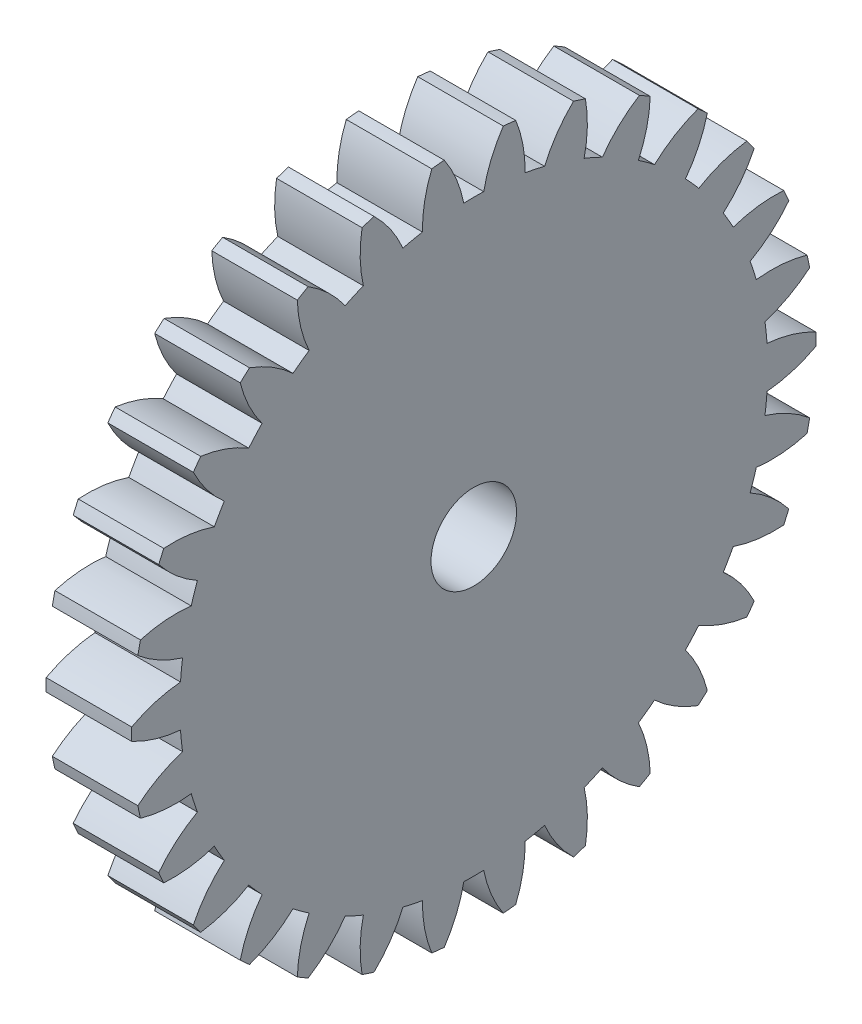
SolidWorks part; units mm, degrees
ref_plane "Plane1" through (0, 0, 0) normal (0, 0, 1) x (1, 0, 0)
ref_plane "Plane2" through (0, 0, 0) normal (0, 1, 0) x (1, 0, 0)
ref_plane "Plane3" through (0, 0, 0) normal (1, 0, 0) x (0, 0, -1)
other "Configuration Table"
sketch "HoldingSke" plane through (0, 0, 0) normal (0, 1, 0) x (1, 0, 0)
  line L0 (0, 0) -> (0.866, -0.5)
  line L1 (-15, 0) -> (100, 0) construction
  line L2 (0, 0) -> (-2.1039, 2.3779)
  line L3 (0, 0) -> (-11.863, 4.5341)
  line L4 (0, 0) -> (7.479, 4.318)
  line L5 (0, 0) -> (-46.8476, -17.4728)
  line L6 (0, 0) -> (-3.3159, -2.2372)
  line L7 (-2.1039, 2.3779) -> (8.6586, 51.2059)
  line L8 (-76.2, 54.61) -> (-75.5, 54.61)
  line L9 (-71.009, 38.7566) -> (-53.1078, 45.2721)
  line L10 (-76.2, 71.12) -> (104.1128, 71.12)
  line L11 (0, 0) -> (-4, 0)
  line L12 (-76.2, 101.6) -> (-76.162, 101.6)
  line L13 (24.9733, 27.94) -> (52.9518, 28.4284)
  line L14 (24.9733, 27.94) -> (24.9743, 27.94)
  line L15 (24.9733, 27.94) -> (100.4006, 29.5858)
  line L16 (-63.627, -1) -> (-12.827, -1)
  circle A0 centre (0, 0) radius 2
  circle A1 centre (0, 0) radius 13.749
  circle A2 centre (0, 0) radius 37.5
  circle A3 centre (0, 0) radius 2
  dimension "MHD" = 27.498
  dimension "Hub_dia" = 75
  dimension "Bore" = 4
  dimension "MBD" = 4
  dimension "Num_teeth" = 30
  dimension "Pitch" = 1
  dimension "Overall_len" = 50
  dimension "Show_teeth" = 30
  dimension "Thickness" = 4
  dimension "OAL" = 50.0001
  dimension "T_dim" = 0.7
  dimension "Ap" = 20
  dimension "H" = 19.05
  dimension "Pitch_radius" = 180.3128
  dimension "Width" = 4
  dimension "Backlash" = 0.038
  dimension "Addendum_fac" = 1
  dimension "Dedendum_fac" = 1.25
  dimension "Clearance_fac" = 0.25
  dimension "Dedendum_add" = 0.001
  dimension "Module" = 1
sketch "BasProSke" plane through (0, 0, 0) normal (0, 1, 0) x (1, 0, 0)
  line L0 (-10, 0) -> (60, 0) construction
  line L1 (0, 0) -> (0, 16)
  line L2 (0, 0) -> (4, 0)
  line L3 (4, 0) -> (4, 16)
  line L4 (4, 16) -> (0, 16)
  dimension "Thickness" = 4
  dimension "Diameter" = 32
revolve "Base-Revolve" add sketch "BasProSke" angle 360 about L0
sketch "TooCutSke" plane through (0, 0, 0) normal (1, 0, 0) x (0, 0, -1)
  line L1 (0, 0) -> (0, 107) construction
  line L2 (0, 0) -> (-0.8515, 14.9758) construction
  line L3 (0, 0) -> (-3.1323, 29.8014) construction
  line L4 (-0.8515, 14.9758) -> (-1.5661, 14.9007) construction
  arc A0 (0.4664, 13.7411) -> (-0.4664, 13.7411) centre (0, 0) ccw
  arc A1 (1.3975, 15.9644) -> (-1.3975, 15.9644) centre (0, 0) ccw
  circle A2 centre (0, 0) radius 15 construction
  circle A3 centre (0, 0) radius 14.0954 construction
  arc A4 (-0.4664, 13.7411) -> (-1.3975, 15.9644) centre (-6.3534, 12.5823) ccw
  arc A5 (1.3975, 15.9644) -> (0.4664, 13.7411) centre (6.3534, 12.5823) ccw
  dimension "Root_dia" = 27.498
  dimension "Overcut_dia" = 32.0508
  dimension "Pitch_dia" = 30
  dimension "Base_dia" = 28.1908
  dimension "Flank_rad" = 6
  dimension "Half_ang" = 6
  dimension "Half_CT" = 0.7185
extrude "ToothCut" cut sketch "TooCutSke" along normal through all
fillet "Breaks" [suppressed] radius 0.02
fillet "RootFillets" [suppressed] radius 0.251
pattern_circular "TeethCuts" count 30 every 12 about axis through (-10, 0, 0) along (1, 0, 0) of "ToothCut", "RootFillets", "Breaks"
sketch "HubNeaOneSke" plane through (0, 0, 0) normal (-1, 0, 0) x (0, 0, 1)
  circle A0 centre (0, 0) radius 13.749
  dimension "Diameter" = 27.498
extrude "HubNearOne" [suppressed] add sketch "HubNeaOneSke" along normal blind 46.0001
sketch "HubNeaBotSke" plane through (0, 0, 0) normal (-1, 0, 0) x (0, 0, 1)
  circle A0 centre (0, 0) radius 13.749
  dimension "Diameter" = 27.498
extrude "HubNearBoth" [suppressed] add sketch "HubNeaBotSke" along normal blind 23
ref_plane "FarPln" through (4, 0, 0) normal (1, 0, 0) x (0, 0, -1)
sketch "HubFarSke" plane through (4, 0, 0) normal (1, 0, 0) x (0, 0, -1)
  circle A0 centre (0, 0) radius 13.749
  dimension "Diameter" = 27.498
extrude "HubFar" [suppressed] add sketch "HubFarSke" along normal blind 23
sketch "BorSke" plane through (0, 0, 0) normal (1, 0, 0) x (0, 0, -1)
  circle A0 centre (0, 0) radius 2
  dimension "Diameter" = 4
extrude "Bore" cut sketch "BorSke" along normal mid plane 100.0001
sketch "KeySke" plane through (0, 0, 0) normal (1, 0, 0) x (0, 0, -1)
  line L0 (-0.8, 0) -> (-0.8, 2.7)
  line L1 (-0.8, 2.7) -> (0.8, 2.7)
  line L2 (0.8, 2.7) -> (0.8, 0)
  line L3 (0, 0) -> (0, 34) construction
  line L4 (-0.8, 0) -> (0.8, 0)
  dimension "Offset" = 2.7
  dimension "Width" = 1.6
extrude "Keyway" [suppressed] cut sketch "KeySke" along normal mid plane 100.0001
pattern_circular "Keyway2" [suppressed] count 2 every 90 about axis through (-10, 0, 0) along (1, 0, 0)
equation "' \"Module@HoldingSke\" = 6.35"
equation "' \"Num_teeth@HoldingSke\" = 12"
equation "' \"Ap@HoldingSke\" =  20"
equation "' \"Ap@HoldingSke\" = 20"
equation "' \"Width@HoldingSke\" = 0.5 * 25.4"
equation "' \"Hub_dia@HoldingSke\"= 1 * 25.4"
equation "' \"Hub_dia@HoldingSke\" = 1 * 25.4"
equation "' \"Overall_len@HoldingSke\" = 1.0 * 25.4"
equation "' \"Bore@HoldingSke\" = 0.75 * 25.4"
equation "' \"T_dim@HoldingSke\" = 0.1 * 25.4"
equation "' \"Width@KeySke\" = 0.25 * 25.4"
equation "' \"Show_teeth@HoldingSke\" = 13"
equation "' \"Backlash@HoldingSke\" = 0.009 * 25.4"
equation "' \"Addendum_fac@HoldingSke\" = 1.0"
equation "' \"Dedendum_fac@HoldingSke\" = 1.25"
equation "' \"Dedendum_add@HoldingSke\" = 0.00005 * 25.4"
equation "' \"Clearance_fac@HoldingSke\" = 0.25"
equation "\"Pitch@HoldingSke\" = 1 / \"Module@HoldingSke\""
equation "\"Overcut_dia@TooCutSke\" = (\"Num_teeth@HoldingSke\" + 2 * \"Addendum_fac@HoldingSke\") / \"Pitch@HoldingSke\" + 0.002 * 25.4"
equation "\"Pitch_dia@TooCutSke\" = \"Num_teeth@HoldingSke\" / \"Pitch@HoldingSke\""
equation "\"Base_dia@TooCutSke\" = \"Num_teeth@HoldingSke\" / \"Pitch@HoldingSke\" * cos((\"Ap@HoldingSke\"  * 3.14159265 / 180))"
equation "\"Root_dia@TooCutSke\" = (\"Num_teeth@HoldingSke\" + 2) / \"Pitch@HoldingSke\" - 2 * (\"Addendum_fac@HoldingSke\" + \"Dedendum_fac@HoldingSke\") / \"Pitch@HoldingSke\" - \"Dedendum_add@HoldingSke\" * 2"
equation "\"Half_ang@TooCutSke\" = 180 / \"Num_teeth@HoldingSke\""
equation "\"Half_CT@TooCutSke\" = \"Num_teeth@HoldingSke\" / \"Pitch@HoldingSke\" * sin((3.14159265 / 2 / \"Num_teeth@HoldingSke\")) / 2 - 7 * \"Backlash@HoldingSke\" / 4"
equation "\"Flank_rad@TooCutSke\" = \"Num_teeth@HoldingSke\" / \"Pitch@HoldingSke\" / 5"
equation "\"Radius@RootFillets\" = \"Clearance_fac@HoldingSke\" / \"Pitch@HoldingSke\" + \"Dedendum_add@HoldingSke\""
equation "\"Break_rad@Breaks\" = 0.02 / \"Pitch@HoldingSke\""
equation "\"Thickness@HoldingSke\" = \"Width@HoldingSke\""
equation "\"OAL@HoldingSke\" = \"Thickness@HoldingSke\""
equation "\"MHD@HoldingSke\" = (\"Num_teeth@HoldingSke\" + 2) / \"Pitch@HoldingSke\" - 2 * (\"Addendum_fac@HoldingSke\" + \"Dedendum_fac@HoldingSke\")  / \"Pitch@HoldingSke\" - \"Dedendum_add@HoldingSke\" * 2"
equation "\"MBD@HoldingSke\" = (\"Num_teeth@HoldingSke\" + 2) / \"Pitch@HoldingSke\" - 2 * (\"Addendum_fac@HoldingSke\" + \"Dedendum_fac@HoldingSke\")  / \"Pitch@HoldingSke\" - \"Dedendum_add@HoldingSke\" * 2 - 0.002 * 25.4"
equation "\"MHD@HoldingSke\" = ((sgn( \"MHD@HoldingSke\" - \"Hub_dia@HoldingSke\" )-1)*( \"MHD@HoldingSke\" - \"Hub_dia@HoldingSke\" ))/-2+ \"Hub_dia@HoldingSke\""
equation "\"MBD@HoldingSke\" = ((sgn( \"MBD@HoldingSke\" - \"Bore@HoldingSke\" )-1)*( \"MBD@HoldingSke\" - \"Bore@HoldingSke\" ))/-2+ \"Bore@HoldingSke\""
equation "\"OAL@HoldingSke\" = ((sgn( \"OAL@HoldingSke\" - \"Overall_len@HoldingSke\" )+1)*( \"OAL@HoldingSke\" - \"Overall_len@HoldingSke\" ))/2 + \"Overall_len@HoldingSke\" + 0.000002 * 25.4"
equation "\"Num_teeth@TeethCuts\" = int( \"Show_teeth@HoldingSke\" ) + 1"
equation "\"Num_teeth@TeethCuts\" = ((sgn( \"Num_teeth@TeethCuts\" - \"Num_teeth@HoldingSke\" )-1)*( \"Num_teeth@TeethCuts\" - \"Num_teeth@HoldingSke\" ))/-2+ \"Num_teeth@HoldingSke\""
equation "\"Num_teeth@TeethCuts\" = ((sgn( \"Num_teeth@TeethCuts\" - 2.0)+1)*( \"Num_teeth@TeethCuts\" - 2.0))/2 +2.0"
equation "\"Angle@TeethCuts\" = 360.0 / \"Num_teeth@HoldingSke\""
equation "\"Diameter@BasProSke\" = (\"Num_teeth@HoldingSke\" + 2 * \"Addendum_fac@HoldingSke\") / \"Pitch@HoldingSke\""
equation "\"Thickness@BasProSke\"  = \"Thickness@HoldingSke\""
equation "' \"Fillet_rad@BasProSke\" =  \"Thickness@HoldingSke\" * 0.05"
equation "' \"Fillet_rad@BasProSke\" = \"Thickness@HoldingSke\" * 0.05"
equation "\"MHD@HoldingSke\" = ((sgn( \"MHD@HoldingSke\" - \"Root_dia@TooCutSke\" )-1)*( \"MHD@HoldingSke\" - \"Root_dia@TooCutSke\" ))/-2+ \"Root_dia@TooCutSke\""
equation "\"Diameter@HubNeaOneSke\" = \"MHD@HoldingSke\""
equation "\"Length@HubNearOne\" = \"OAL@HoldingSke\" - \"Thickness@BasProSke\""
equation "\"Diameter@HubNeaBotSke\" = \"MHD@HoldingSke\""
equation "\"Length@HubNearBoth\" = ( \"OAL@HoldingSke\" - \"Thickness@BasProSke\" ) / 2.0"
equation "\"Thickness@FarPln\" = \"Thickness@BasProSke\""
equation "\"Diameter@HubFarSke\" = \"MHD@HoldingSke\""
equation "\"Length@HubFar\" = ( \"OAL@HoldingSke\" - \"Thickness@BasProSke\" ) / 2.0"
equation "\"Diameter@BorSke\" = \"MBD@HoldingSke\""
equation "\"D1@Bore\" = \"OAL@HoldingSke\" * 2.0"
equation "\"D1@Keyway\" = \"OAL@HoldingSke\" * 2.0"
equation "\"Offset@KeySke\" = \"T_dim@HoldingSke\" + \"MBD@HoldingSke\" / 2.0"
